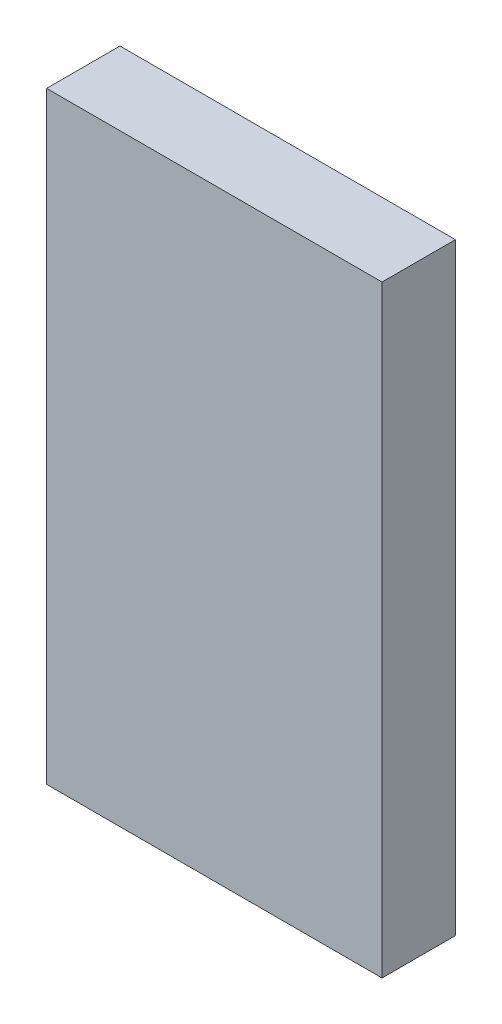
SolidWorks part; units mm, degrees
ref_plane "Front Plane" through (0, 0, 0) normal (0, 0, 1) x (1, 0, 0)
ref_plane "Top Plane" through (0, 0, 0) normal (0, 1, 0) x (1, 0, 0)
ref_plane "Right Plane" through (0, 0, 0) normal (1, 0, 0) x (0, 0, -1)
sketch "Sketch1" plane through (0, 0, 0) normal (0, 0, 1) x (1, 0, 0)
  line L1 (0, 0) -> (12.8, 0)
  line L2 (0, 0) -> (0, 23)
  line L3 (0, 23) -> (12.8, 23)
  line L4 (12.8, 0) -> (12.8, 23)
  dimension "D1" = 23
  dimension "D2" = 12.8
extrude "Boss-Extrude1" add sketch "Sketch1" along normal blind 2.8
